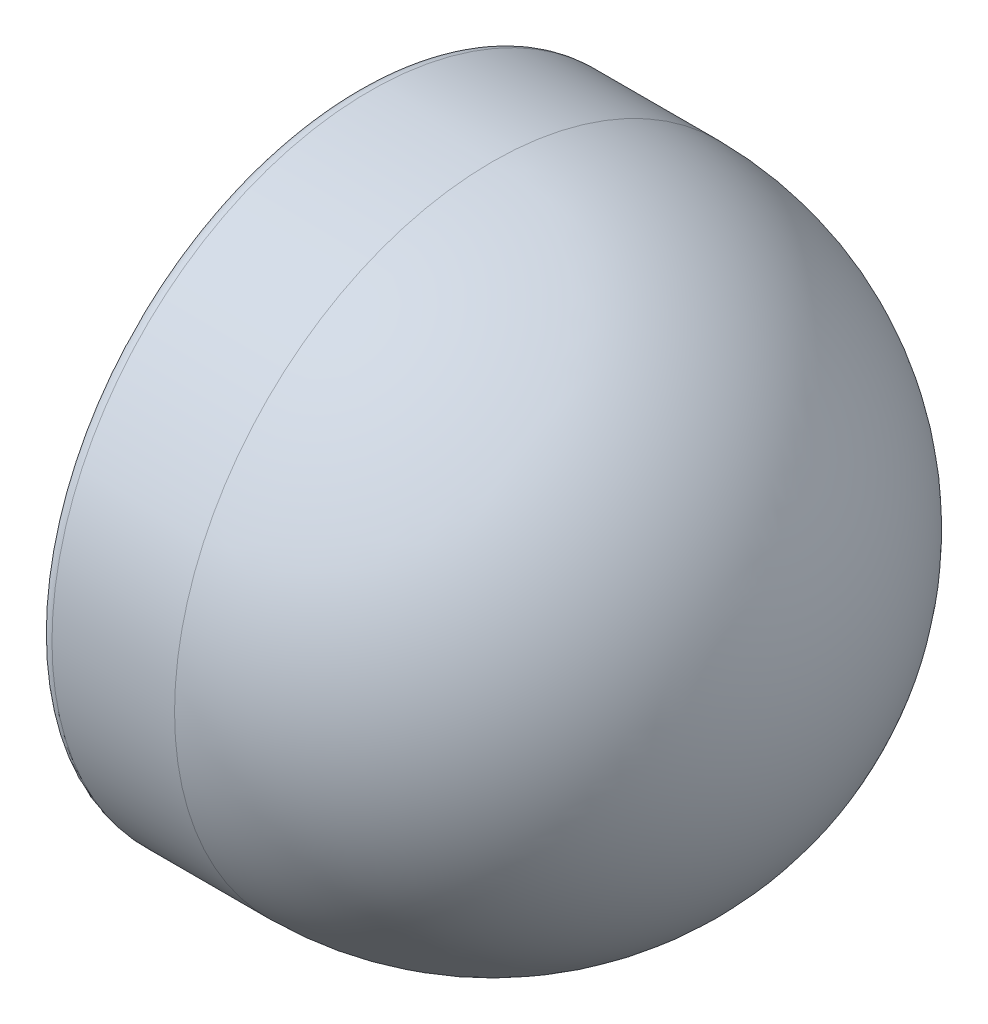
SolidWorks part; units mm, degrees
ref_plane "Front Plane" through (0, 0, 0) normal (0, 0, 1) x (1, 0, 0)
ref_plane "Top Plane" through (0, 0, 0) normal (0, 1, 0) x (1, 0, 0)
ref_plane "Right Plane" through (0, 0, 0) normal (1, 0, 0) x (0, 0, -1)
sketch "Sketch1" plane through (0, 0, 0) normal (0, 0, 1) x (1, 0, 0)
  line L0 (-70, 0) -> (70.5297, 0) construction
  line L1 (-70, 70) -> (-97, 70)
  line L2 (-100, 67) -> (-100, 61.5)
  line L3 (-98.5, 60) -> (-96.6213, 60)
  line L4 (-95.5607, 60.4393) -> (-92, 64)
  line L5 (-70, 69) -> (-97, 69)
  line L6 (-99, 67) -> (-99, 61.5)
  line L7 (-98.5, 61) -> (-96.6213, 61)
  line L8 (-96.2678, 61.1464) -> (-92.7071, 64.7071)
  line L9 (-92, 64) -> (-92, 64.7071)
  line L10 (-92, 64.7071) -> (-92.7071, 64.7071)
  line L11 (-1, 0) -> (0, 0)
  arc A0 (0, 0) -> (-70, 70) centre (-70, 0) ccw
  arc A1 (-97, 70) -> (-100, 67) centre (-97, 67) ccw
  arc A2 (-96.6213, 60) -> (-95.5607, 60.4393) centre (-96.6213, 61.5) ccw
  arc A3 (-100, 61.5) -> (-98.5, 60) centre (-98.5, 61.5) ccw
  arc A4 (-1, 0) -> (-70, 69) centre (-70, 0) ccw
  arc A5 (-97, 69) -> (-99, 67) centre (-97, 67) ccw
  arc A6 (-99, 61.5) -> (-98.5, 61) centre (-98.5, 61.5) ccw
  arc A7 (-96.6213, 61) -> (-96.2678, 61.1464) centre (-96.6213, 61.5) ccw
  point P12 (-100, 70)
  point P15 (-96, 60)
  point P18 (-100, 60)
  dimension "D1" = 70
  dimension "D6" = 3
  dimension "D7" = 1.5
  dimension "D2" = 30
  dimension "D3" = 10
  dimension "D4" = 4
  dimension "D5" = 135
  dimension "D9" = 7
  dimension "D8" = 1
revolve "Revolve1" add sketch "Sketch1" angle 360 about L0
